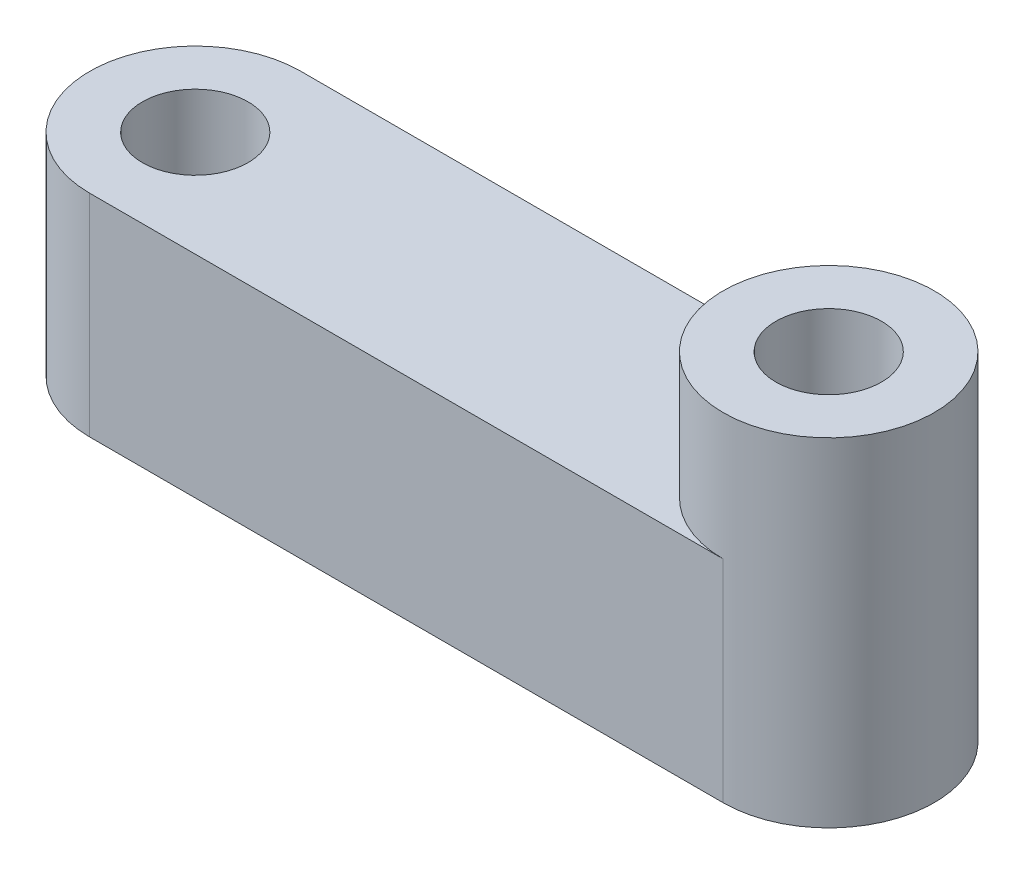
SolidWorks part; units mm, degrees
ref_plane "Front Plane" through (0, 0, 0) normal (0, 0, 1) x (1, 0, 0)
ref_plane "Top Plane" through (0, 0, 0) normal (0, 1, 0) x (1, 0, 0)
ref_plane "Right Plane" through (0, 0, 0) normal (1, 0, 0) x (0, 0, -1)
sketch "Sketch1" plane through (0, 0, 0) normal (0, 1, 0) x (1, 0, 0)
  line L0 (0, 0) -> (30, 0) construction
  line L1 (0, 5) -> (30, 5)
  line L2 (0, -5) -> (30, -5)
  arc A0 (0, 5) -> (0, -5) centre (0, 0) ccw
  arc A1 (30, -5) -> (30, 5) centre (30, 0) ccw
  circle A2 centre (0, 0) radius 2.5
  circle A3 centre (30, 0) radius 2.5
  point P3 (15, 0)
  dimension "D3" = 5
  dimension "D4" = 5
  dimension "D1" = 30
  dimension "D2" = 10
extrude "Boss-Extrude1" add sketch "Sketch1" along normal blind 4 and the other way blind 6
ref_plane "Plane1" through (0, -1, 0) normal (0, 1, 0) x (1, 0, 0)
sketch "Sketch3" plane through (0, -1, 0) normal (0, 1, 0) x (1, 0, 0)
  circle A0 centre (30, 0) radius 5
  circle A1 centre (30, 0) radius 2.5
extrude "Boss-Extrude3" add sketch "Sketch3" along normal blind 11 and the other way blind 5
sketch "Sketch4" plane through (0, 4, 0) normal (0, 1, 0) x (1, 0, 0)
  line L0 (15, 5) -> (15, 0) construction
  line L1 (30, 5) -> (0, 5) construction
  line L3 (10.8195, 0) -> (18.4441, 0) construction
  line L4 (12.0283, 2.5) -> (17.5608, 2.5) construction
  line L5 (15, 0) -> (15, -5) construction
  line L6 (0, -5) -> (30, -5) construction
  line L7 (12.0283, -2.5) -> (17.5608, -2.5) construction
  line L8 (0, -5) -> (30, -5)
  line L9 (0, 5) -> (30, 5)
  arc A0 (2.7717, 4.1615) -> (0, 5) centre (0, 0) ccw
  arc A1 (34.7703, -1.4981) -> (30, -5) centre (30, 0) ccw
  arc A2 (0, -5) -> (2.7717, -4.1615) centre (0, 0) ccw
  arc A3 (30, 5) -> (34.7703, 1.4981) centre (30, 0) ccw
  spline S0 degree 3 poles (2.7717, 4.1615) (6.8478, 3.0538) (11.229, 3.2779) (30.6942, 0.3904) (34.7703, 1.4981) knots 0.092389 0.092389 0.092389 0.092389 0.5 0.907611 0.907611 0.907611 0.907611
  spline S1 degree 3 poles (2.7717, -4.1615) (6.8478, -3.0538) (11.229, -3.2779) (30.6942, -0.3904) (34.7703, -1.4981) knots 0.092389 0.092389 0.092389 0.092389 0.5 0.907611 0.907611 0.907611 0.907611
